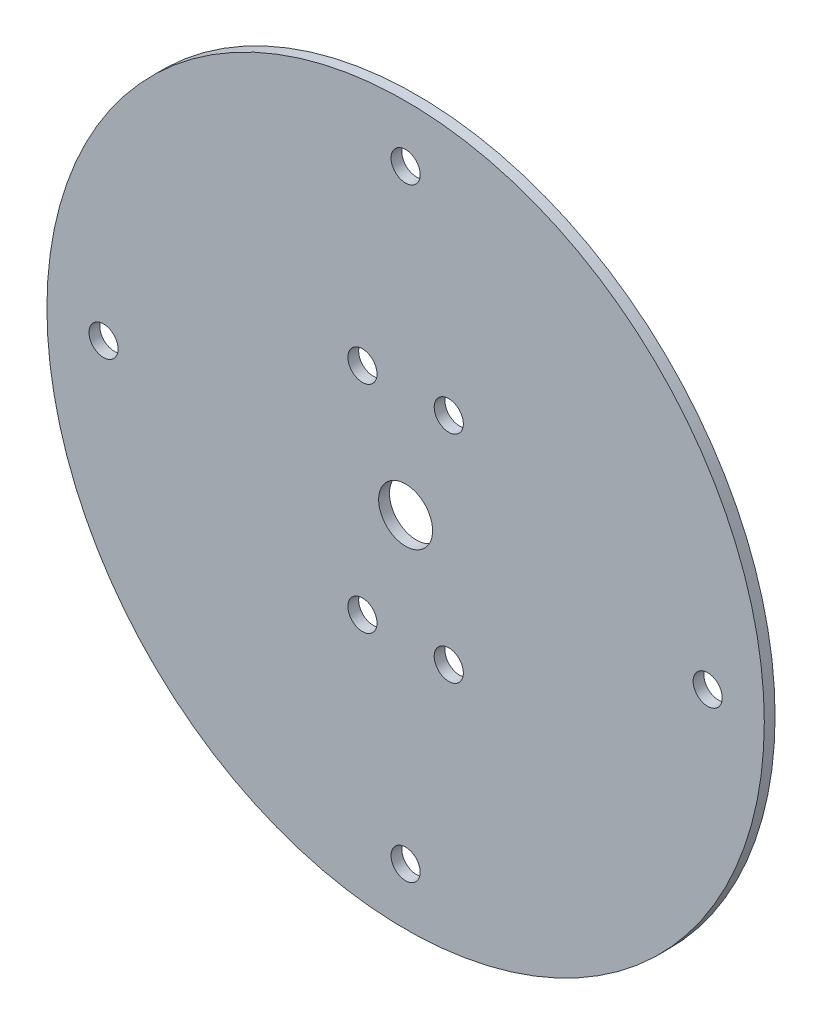
SolidWorks part; units mm, degrees
ref_plane "Front Plane" through (0, 0, 0) normal (0, 0, 1) x (1, 0, 0)
ref_plane "Top Plane" through (0, 0, 0) normal (0, 1, 0) x (1, 0, 0)
ref_plane "Right Plane" through (0, 0, 0) normal (1, 0, 0) x (0, 0, -1)
sketch "Sketch1" plane through (0, 0, 0) normal (0, 0, 1) x (1, 0, 0)
  circle A0 centre (0, 0) radius 84.455
  dimension "D1" = 168.91
extrude "Boss-Extrude1" add sketch "Sketch1" along normal blind 2.54
sketch "Sketch2" plane through (0, 0, 2.54) normal (0, 0, 1) x (1, 0, 0)
  line L0 (0, 0) -> (60.2509, 0) construction
  line L1 (0, 0) -> (0, 49.4395) construction
  circle A0 centre (0, 0) radius 12.7 construction
  circle A1 centre (-10.16, 25.4) radius 3.429
  circle A2 centre (10.16, 25.4) radius 3.429
  circle A3 centre (10.16, -25.4) radius 3.429
  circle A4 centre (-10.16, -25.4) radius 3.429
  dimension "D1" = 25.4
  dimension "D2" = 6.858
  dimension "D3" = 25.4
  dimension "D4" = 10.16
extrude "Cut-Extrude1" cut sketch "Sketch2" against normal blind 2.54
sketch "Sketch3" plane through (0, 0, 2.54) normal (0, 0, 1) x (1, 0, 0)
  circle A0 centre (0, 0) radius 6.35
  dimension "D1" = 12.7
extrude "Cut-Extrude2" cut sketch "Sketch3" against normal blind 2.54
sketch "Sketch4" plane through (0, 0, 0) normal (0, 0, -1) x (-1, 0, 0)
  line L0 (71.12, 0) -> (50.7907, 0) construction
  circle A0 centre (71.12, 0) radius 3.429
  dimension "D1" = 6.858
  dimension "D2" = 71.12
extrude "Cut-Extrude3" cut sketch "Sketch4" against normal through all
pattern_circular "CirPattern1" count 4 over 360 about axis through (0, 0, 0) along (0, 0, 1) of "Cut-Extrude3"
equation "\"chainring_bolt_dia\"=0.27"
equation "\"D1@Sketch4\"=\"chainring_bolt_dia\""
equation "\"chainring_bolt_hole_rad\"=2.8"
equation "\"D2@Sketch4\"=\"chainring_bolt_hole_rad\""
equation "\"num_chainring\" = 4"
equation "\"D1@CirPattern1\"=\"num_chainring\""
